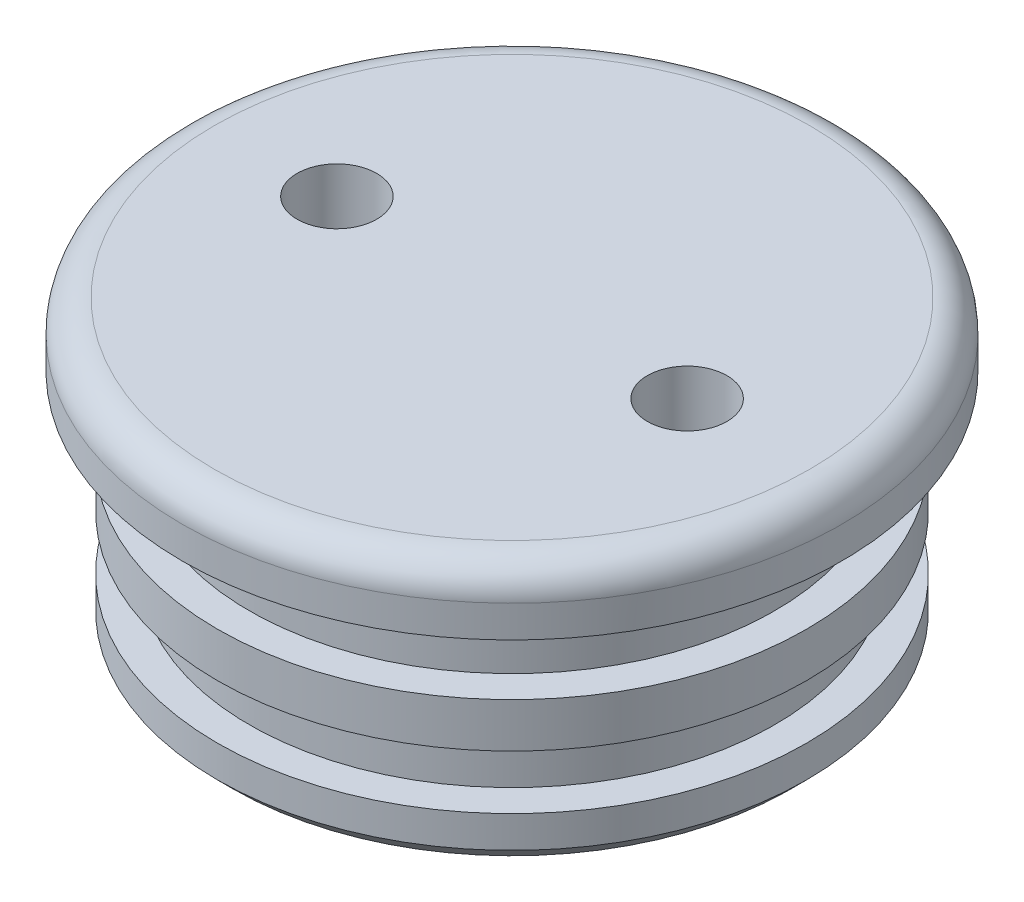
SolidWorks part; units mm, degrees
ref_plane "前视基准面" through (0, 0, 0) normal (0, 0, 1) x (1, 0, 0)
ref_plane "上视基准面" through (0, 0, 0) normal (0, 1, 0) x (1, 0, 0)
ref_plane "右视基准面" through (0, 0, 0) normal (1, 0, 0) x (0, 0, -1)
sketch "草图1" plane through (0, 0, 0) normal (0, 1, 0) x (1, 0, 0)
  circle A0 centre (0, 0) radius 11
  dimension "D1" = 22
extrude "凸台-拉伸1" add sketch "草图1" along normal blind 9
sketch "草图2" plane through (0, 9, 0) normal (0, 1, 0) x (1, 0, 0)
  circle A0 centre (-5.5, 0) radius 0.5
  circle A1 centre (5.5, 0) radius 0.5
  dimension "D1" = 1
  dimension "D2" = 1
  dimension "D3" = 11
  dimension "D4" = 5.5
extrude "切除-拉伸1" cut sketch "草图2" against normal through all
sketch "草图3" plane through (0, 0, 0) normal (0, -1, 0) x (1, 0, 0)
  circle A0 centre (0, 0) radius 9.25
  circle A1 centre (0, 0) radius 16.5491
  dimension "D1" = 18.5
extrude "切除-拉伸2" cut sketch "草图3" against normal blind 7
sketch "草图4" plane through (0, 0, 0) normal (0, 0, 1) x (1, 0, 0)
  line L0 (-9.25, 7) -> (-9.25, 0) construction
  line L1 (-10.25, 6.3) -> (-8.25, 6.3)
  line L2 (-10.25, 6.3) -> (-10.25, 4.6)
  line L3 (-10.25, 4.6) -> (-8.25, 4.6)
  line L4 (-8.25, 6.3) -> (-8.25, 4.6)
  line L5 (-10.25, 6.3) -> (-8.25, 4.6) construction
  line L6 (-10.25, 4.6) -> (-8.25, 6.3) construction
  line L7 (-9.25, 0) -> (9.25, 0) construction
  line L8 (-10.25, 3.2) -> (-8.25, 3.2)
  line L9 (-10.25, 3.2) -> (-10.25, 1.5)
  line L10 (-10.25, 1.5) -> (-8.25, 1.5)
  line L11 (-8.25, 3.2) -> (-8.25, 1.5)
  line L12 (-10.25, 3.2) -> (-8.25, 1.5) construction
  line L13 (-10.25, 1.5) -> (-8.25, 3.2) construction
  line L14 (0, 0) -> (0, 12.2991) construction
  point P0 (-9.25, 5.45)
  point P7 (-9.25, 2.35)
  dimension "D1" = 1.7
  dimension "D2" = 1.7
  dimension "D3" = 1.5
  dimension "D4" = 1.4
  dimension "D5" = 2
  dimension "D6" = 2
revolve "切除-旋转1" cut sketch "草图4" angle 360 about L14
sketch "草图5" plane through (0, 0, 0) normal (0, -1, 0) x (1, 0, 0)
  line L1 (-2.5, 3) -> (2.5, 3)
  line L2 (-2.5, 3) -> (-2.5, -3)
  line L3 (-2.5, -3) -> (2.5, -3)
  line L4 (2.5, 3) -> (2.5, -3)
  line L5 (-2.5, 3) -> (2.5, -3) construction
  line L6 (-2.5, -3) -> (2.5, 3) construction
  point P0 (0, 0)
  dimension "D1" = 6
  dimension "D2" = 5
extrude "切除-拉伸3" cut sketch "草图5" against normal blind 7
sketch "草图6" plane through (0, 9, 0) normal (0, 1, 0) x (1, 0, 0)
  circle A0 centre (0, 0) radius 1.4
  dimension "D1" = 2.8
extrude "切除-拉伸4" cut sketch "草图6" against normal blind 7
sketch "草图7" plane through (0, 9, 0) normal (0, 1, 0) x (1, 0, 0)
  circle A0 centre (-5.5, 0) radius 1.25
  circle A1 centre (5.5, 0) radius 1.25
  dimension "D1" = 2.5
  dimension "D2" = 2.5
extrude "切除-拉伸5" cut sketch "草图7" against normal blind 2.5
sketch "草图8" plane through (0, 0, 0) normal (0, -1, 0) x (1, 0, 0)
  circle A0 centre (-5.5, 0) radius 1.25
  circle A1 centre (5.5, 0) radius 1.25
  dimension "D1" = 2.5
  dimension "D2" = 2.5
extrude "切除-拉伸6" cut sketch "草图8" against normal blind 1.5
sketch "草图9" plane through (0, 0, 0) normal (0, -1, 0) x (1, 0, 0)
  line L0 (-2.5, 3) -> (-2.5, -3) construction
  line L1 (2.5, 3) -> (-2.5, 3) construction
  line L2 (2.5, -3) -> (2.5, 3) construction
  line L4 (-2.5, -3) -> (2.5, -3) construction
  line L5 (-2.5, -3) -> (2.5, -3)
  line L6 (2.5, -3) -> (2.5, 3)
  line L7 (2.5, 3) -> (-2.5, 3)
  line L8 (-2.5, 3) -> (-2.5, -3)
  line L9 (3.5, 4) -> (-3.5, 4)
  line L10 (-3.5, 4) -> (-3.5, -4)
  line L11 (-3.5, -4) -> (3.5, -4)
  line L12 (3.5, -4) -> (3.5, 4)
  circle A1 centre (0, 0) radius 9.25
  circle A10 centre (0, 0) radius 9.25
  line M5 (-2.5, 3) -> (2.5, 3)
  line M6 (2.5, 3) -> (2.5, -3)
  line M7 (2.5, -3) -> (-2.5, -3)
  line M8 (-2.5, -3) -> (-2.5, 3)
  dimension "D1" = 0
  dimension "D2" = 1
extrude "切除-拉伸7" cut sketch "草图9" against normal blind 2 contours L11 L12 L9 L10 M8 M5 M6 M7
chamfer "倒角1" distance 0.5 angle 45 1 edges at (0, 0, -9.25)
sketch "草图10" plane through (0, 9, 0) normal (0, 1, 0) x (1, 0, 0)
  circle A0 centre (0, 0) radius 10.35
  circle A1 centre (0, 0) radius 12.5
  dimension "D1" = 20.7
  dimension "D2" = 25
extrude "切除-拉伸8" cut sketch "草图10" against normal blind 10
fillet "圆角1" radius 1 1 edges at (0, 9, 10.35)
sketch "草图11" plane through (0, 9, 0) normal (0, 1, 0) x (1, 0, 0)
  circle A0 centre (0, 0) radius 1.954
extrude "凸台-拉伸2" add sketch "草图11" against normal blind 2
